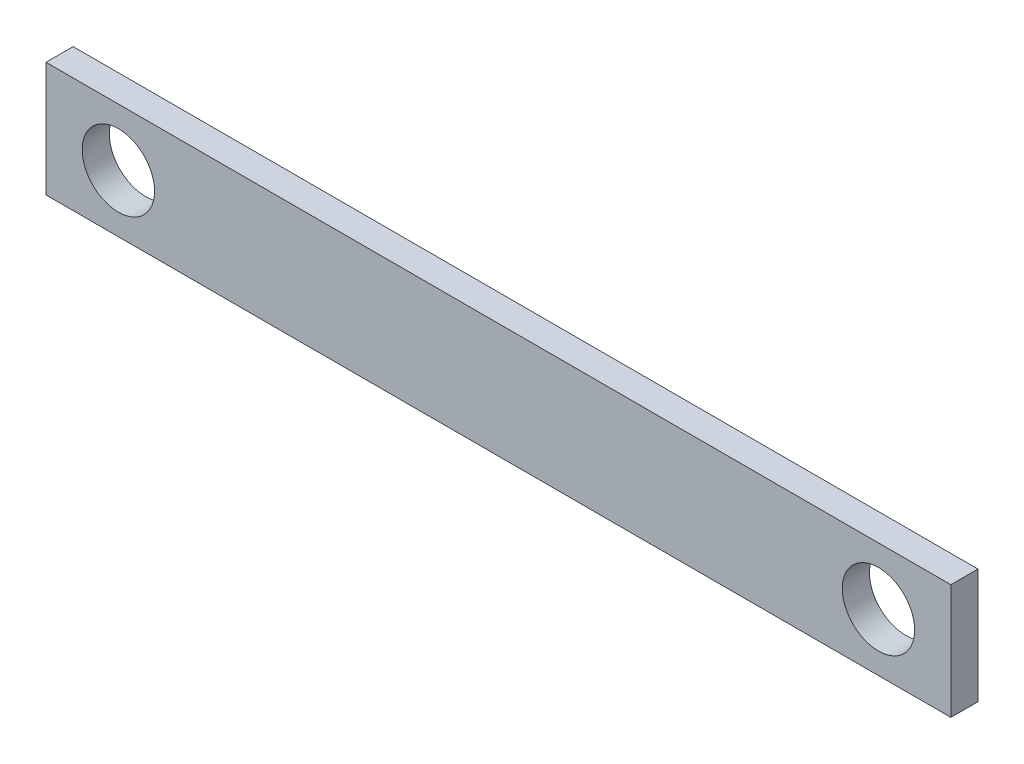
SolidWorks part; units mm, degrees
ref_plane "Alzado" through (0, 0, 0) normal (0, 0, 1) x (1, 0, 0)
ref_plane "Planta" through (0, 0, 0) normal (0, 1, 0) x (1, 0, 0)
ref_plane "Vista lateral" through (0, 0, 0) normal (1, 0, 0) x (0, 0, -1)
sketch "Croquis1" plane through (0, 0, 0) normal (0, 0, 1) x (1, 0, 0)
  line L0 (0, 13.3143) -> (0, -12.8421) construction
  line L1 (50, -6.35) -> (-50, -6.35)
  line L2 (50, -6.35) -> (50, 6.35)
  line L3 (50, 6.35) -> (-50, 6.35)
  line L4 (-50, -6.35) -> (-50, 6.35)
  line L5 (50, -6.35) -> (-50, 6.35) construction
  line L6 (50, 6.35) -> (-50, -6.35) construction
  circle A0 centre (-42, 0) radius 4
  circle A1 centre (42, 0) radius 4
  point P0 (0, 0)
  dimension "D3" = 8
  dimension "D4" = 8
  dimension "D1" = 12.7
  dimension "D2" = 100
extrude "Saliente-Extruir1" add sketch "Croquis1" along normal blind 3
